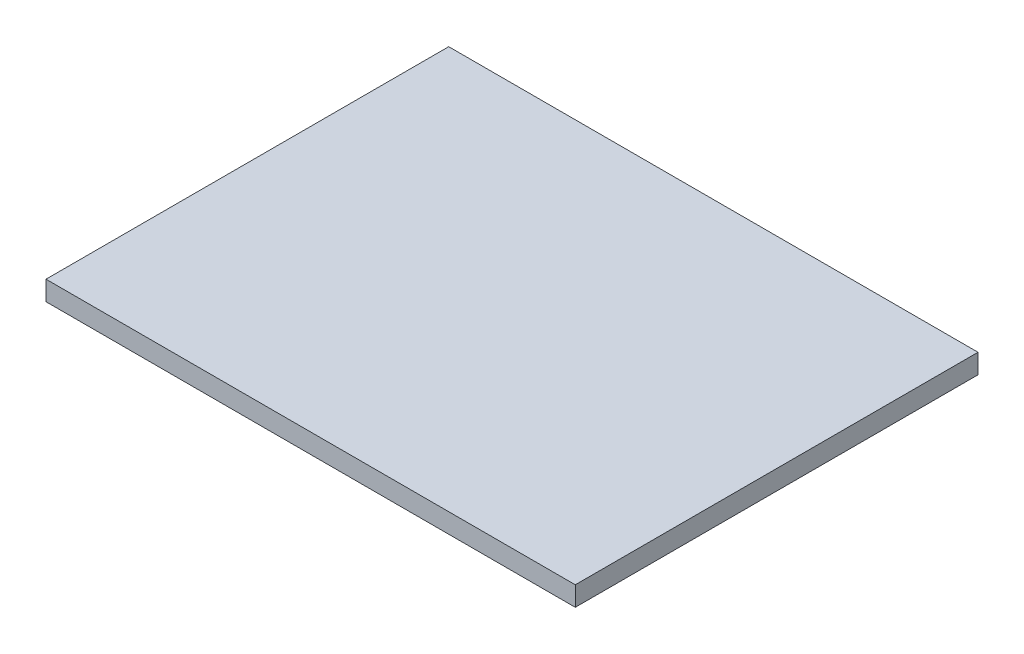
SolidWorks part; units mm, degrees
ref_plane "Front Plane" through (0, 0, 0) normal (0, 0, 1) x (1, 0, 0)
ref_plane "Top Plane" through (0, 0, 0) normal (0, 1, 0) x (1, 0, 0)
ref_plane "Right Plane" through (0, 0, 0) normal (1, 0, 0) x (0, 0, -1)
sketch "Sketch2" plane through (0, 0, 0) normal (0, 1, 0) x (1, 0, 0)
  line L1 (0, 0) -> (68.8013, 0)
  line L2 (0, 0) -> (0, 52.3488)
  line L3 (0, 52.3488) -> (68.8013, 52.3488)
  line L4 (68.8013, 0) -> (68.8013, 52.3488)
  dimension "D1" = 68.8013
extrude "Boss-Extrude1" add sketch "Sketch2" along normal blind 2.54
